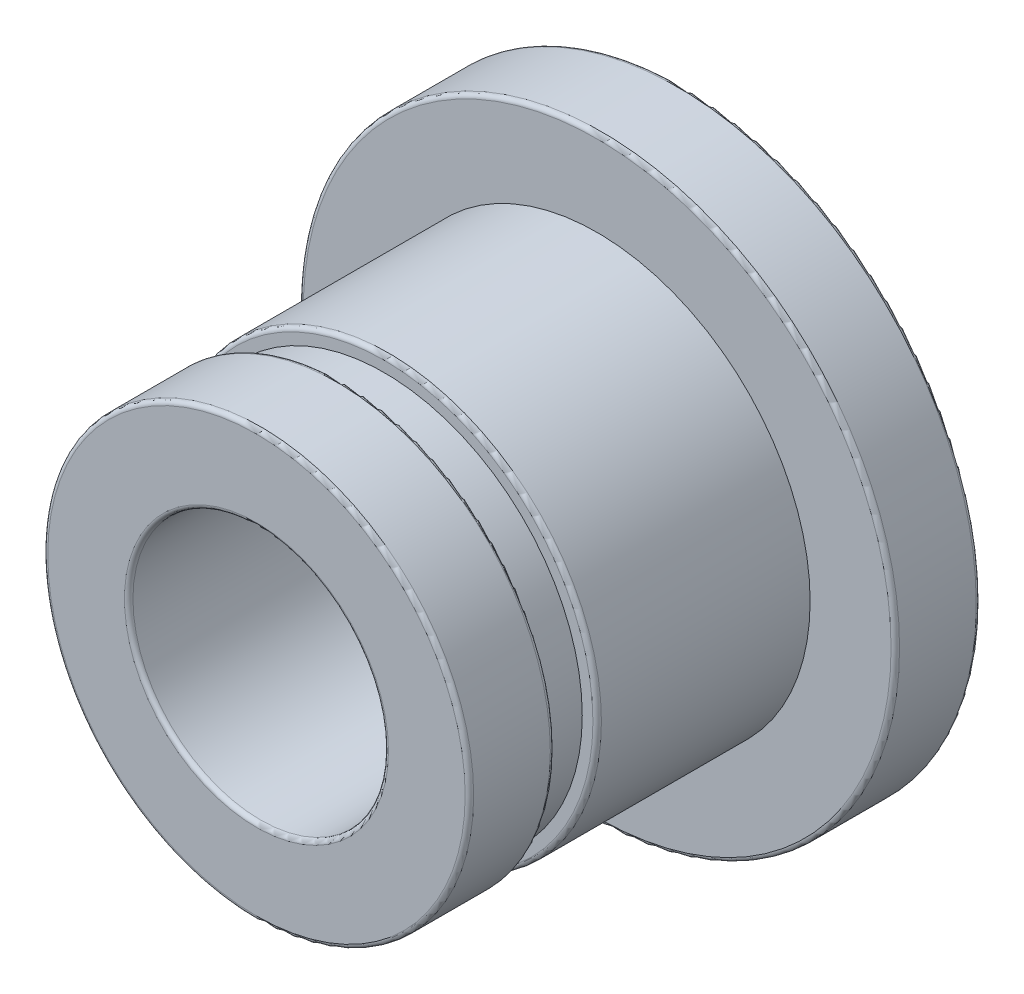
SolidWorks part; units mm, degrees
material "Manganese Bronze"
ref_plane "Front Plane" through (0, 0, 0) normal (0, 0, 1) x (1, 0, 0)
ref_plane "Top Plane" through (0, 0, 0) normal (0, 1, 0) x (1, 0, 0)
ref_plane "Right Plane" through (0, 0, 0) normal (1, 0, 0) x (0, 0, -1)
sketch "Sketch1" plane through (0, 0, 0) normal (0, 0, 1) x (1, 0, 0)
  circle A0 centre (0, 0) radius 7
  dimension "D1" = 14
extrude "Extrude1" add sketch "Sketch1" along normal blind 2
sketch "Sketch2" plane through (0, 0, 2) normal (0, 0, 1) x (1, 0, 0)
  circle A0 centre (0, 0) radius 5
  dimension "D1" = 10
extrude "Extrude2" add sketch "Sketch2" along normal blind 8
sketch "Sketch3" plane through (0, 0, 10) normal (0, 0, 1) x (1, 0, 0)
  circle A0 centre (0, 0) radius 3
  dimension "D1" = 6
extrude "Cut-Extrude1" cut sketch "Sketch3" against normal through all
sketch "Sketch4" plane through (0, 0, 10) normal (0, 0, 1) x (1, 0, 0)
  circle A0 centre (0, 0) radius 4.65
  circle A1 centre (0, 0) radius 5
  circle A4 centre (0, 0) radius 5 construction
  dimension "D1" = 9.3
extrude "Cut-Extrude3" cut sketch "Sketch4" against normal blind 1 from offset 2
fillet "Fillet1" radius 0.1 7 edges at (3, 0, 0) (3, 0, 10) (5, 0, 7) (5, 0, 8) (7, 0, 0) (7, 0, 2) (5, 0, 10)
